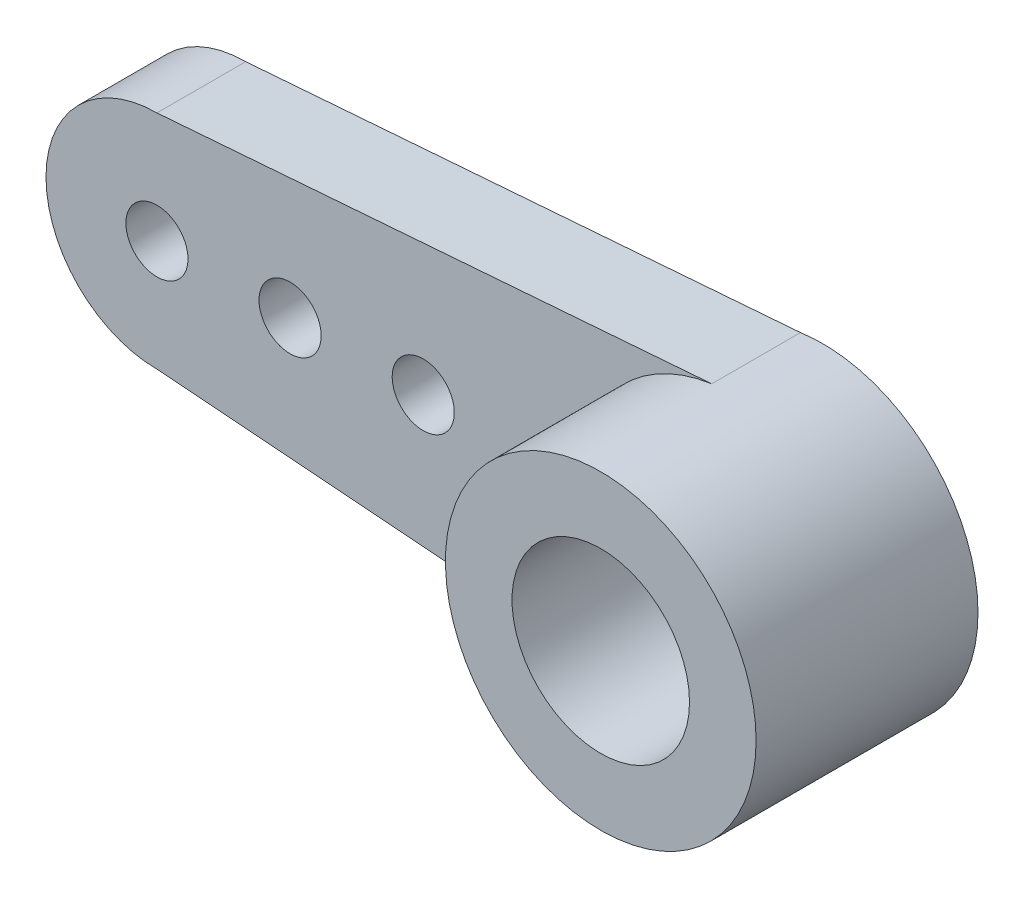
SolidWorks part; units mm, degrees
ref_plane "Front Plane" through (0, 0, 0) normal (0, 0, 1) x (1, 0, 0)
ref_plane "Top Plane" through (0, 0, 0) normal (0, 1, 0) x (1, 0, 0)
ref_plane "Right Plane" through (0, 0, 0) normal (1, 0, 0) x (0, 0, -1)
sketch "Sketch1" plane through (0, 0, 0) normal (0, 0, 1) x (1, 0, 0)
  circle A0 centre (0, 0) radius 3.5
  circle A1 centre (0, 0) radius 2
extrude "Boss-Extrude1" add sketch "Sketch1" along normal blind 5
sketch "Sketch2" plane through (0, 0, 0) normal (0, 0, -1) x (-1, 0, 0)
  line L0 (0, 0) -> (7, 0) construction
  line L1 (2.75, 0) -> (-2.75, 0) construction
  line L2 (7, 0) -> (10, 0) construction
  line L3 (10, 0) -> (13, 0) construction
  line L4 (0.4994, 3.4642) -> (13, 2.5)
  line L5 (0.4994, -3.4642) -> (13, -2.5)
  arc A0 (0.4994, 3.4642) -> (0.4994, -3.4642) centre (0, 0) ccw
  circle A1 centre (0, 0) radius 2
  circle A2 centre (7, 0) radius 0.7
  circle A3 centre (10, 0) radius 0.7
  circle A4 centre (13, 0) radius 0.7
  circle A6 centre (0, 0) radius 3.5 construction
  arc A7 (13, -2.5) -> (13, 2.5) centre (13, 0) ccw
extrude "Boss-Extrude2" add sketch "Sketch2" against normal blind 2
